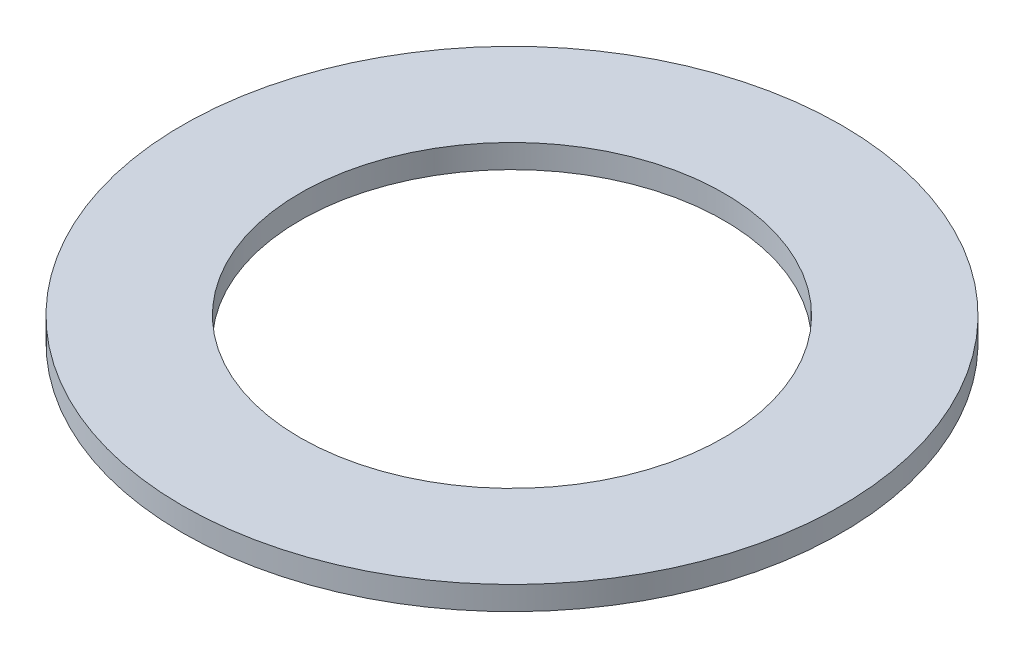
SolidWorks part; units mm, degrees
ref_plane "Front Plane" through (0, 0, 0) normal (0, 0, 1) x (1, 0, 0)
ref_plane "Top Plane" through (0, 0, 0) normal (0, 1, 0) x (1, 0, 0)
ref_plane "Right Plane" through (0, 0, 0) normal (1, 0, 0) x (0, 0, -1)
sketch "Sketch1" plane through (0, 0, 0) normal (0, 1, 0) x (1, 0, 0)
  circle A0 centre (0, 0) radius 4.5
  circle A1 centre (0, 0) radius 7
  dimension "D1" = 9
  dimension "D2" = 14
extrude "Boss-Extrude1" add sketch "Sketch1" along normal blind 0.5
